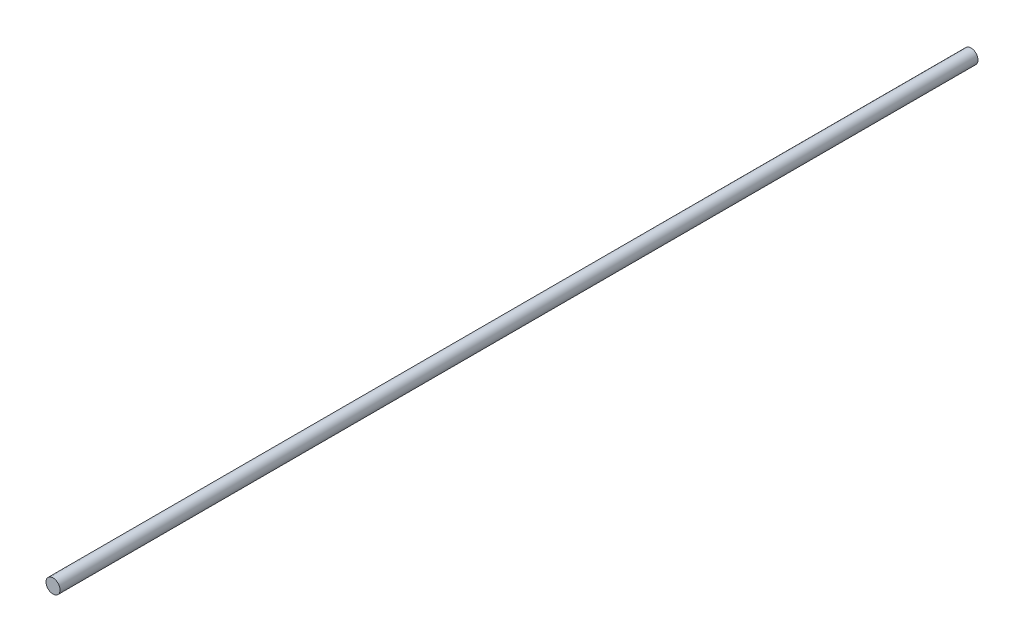
SolidWorks part; units mm, degrees
ref_plane "前视基准面" through (0, 0, 0) normal (0, 0, 1) x (1, 0, 0)
ref_plane "上视基准面" through (0, 0, 0) normal (0, 1, 0) x (1, 0, 0)
ref_plane "右视基准面" through (0, 0, 0) normal (1, 0, 0) x (0, 0, -1)
sketch "草图1" plane through (0, 0, 0) normal (0, 0, 1) x (1, 0, 0)
  circle A0 centre (0, 0) radius 2.5
  dimension "D1" = 5
extrude "凸台-拉伸1" add sketch "草图1" along normal blind 327
